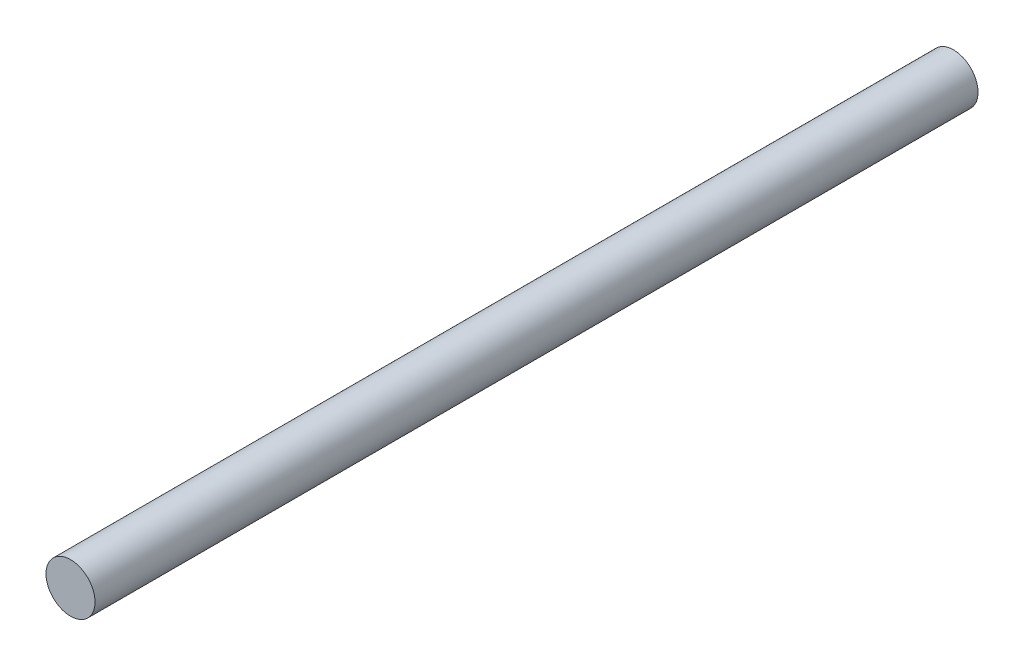
SolidWorks part; units mm, degrees
ref_plane "Front Plane" through (0, 0, 0) normal (0, 0, 1) x (1, 0, 0)
ref_plane "Top Plane" through (0, 0, 0) normal (0, 1, 0) x (1, 0, 0)
ref_plane "Right Plane" through (0, 0, 0) normal (1, 0, 0) x (0, 0, -1)
sketch "Sketch1" plane through (0, 0, 0) normal (0, 0, 1) x (1, 0, 0)
  circle A0 centre (0, 0) radius 2.5
extrude "Boss-Extrude1" add sketch "Sketch1" along normal blind 90
